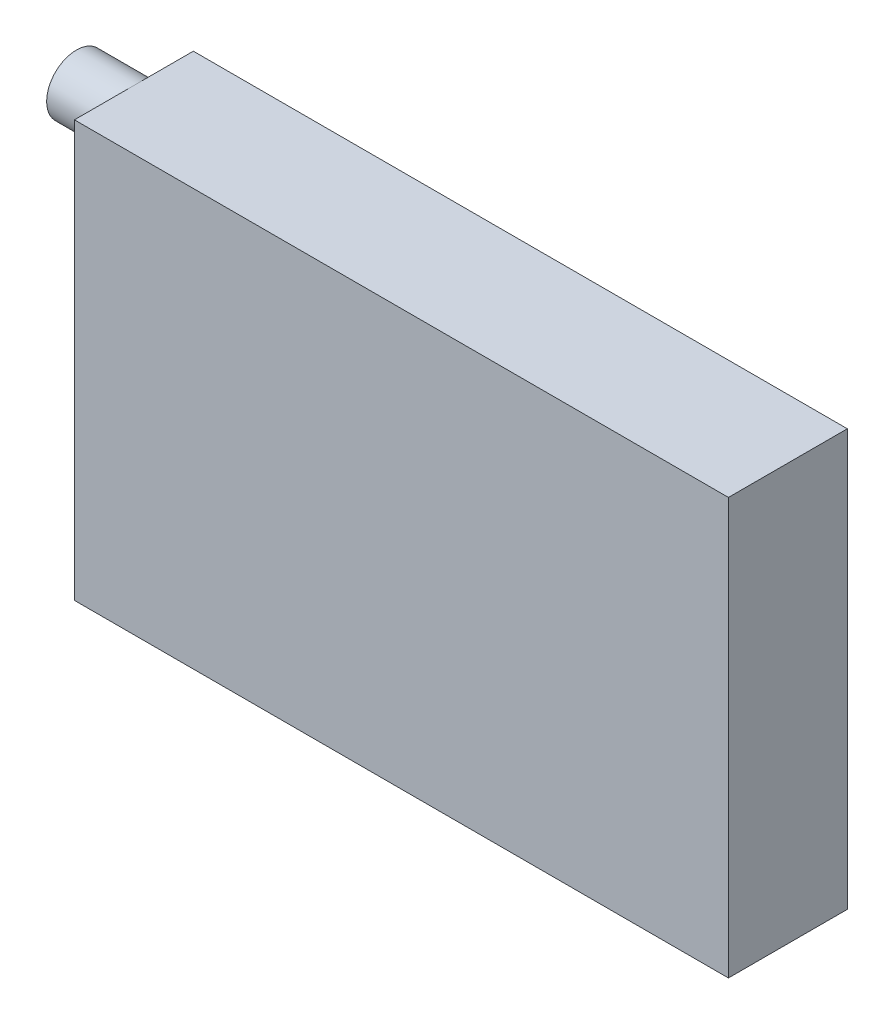
SolidWorks part; units mm, degrees
ref_plane "前视基准面" through (0, 0, 0) normal (0, 0, 1) x (1, 0, 0)
ref_plane "上视基准面" through (0, 0, 0) normal (0, 1, 0) x (1, 0, 0)
ref_plane "右视基准面" through (0, 0, 0) normal (1, 0, 0) x (0, 0, -1)
other "Configuration Table"
sketch "草图1" plane through (0, 0, 0) normal (0, 0, 1) x (1, 0, 0)
  line L1 (-55, 35) -> (55, 35)
  line L2 (-55, 35) -> (-55, -35)
  line L3 (-55, -35) -> (55, -35)
  line L4 (55, 35) -> (55, -35)
  line L5 (-55, 35) -> (55, -35) construction
  line L6 (-55, -35) -> (55, 35) construction
  point P0 (0, 0)
  dimension "D1" = 70
  dimension "D2" = 110
extrude "凸台-拉伸1" add sketch "草图1" along normal blind 20
sketch "草图2" plane through (-55, 0, 0) normal (-1, 0, 0) x (0, 0, 1)
  line L0 (20, 35) -> (0, 35) construction
  circle A0 centre (9.6692, 30) radius 5
  dimension "D1" = 5
extrude "凸台-拉伸2" add sketch "草图2" along normal blind 10
